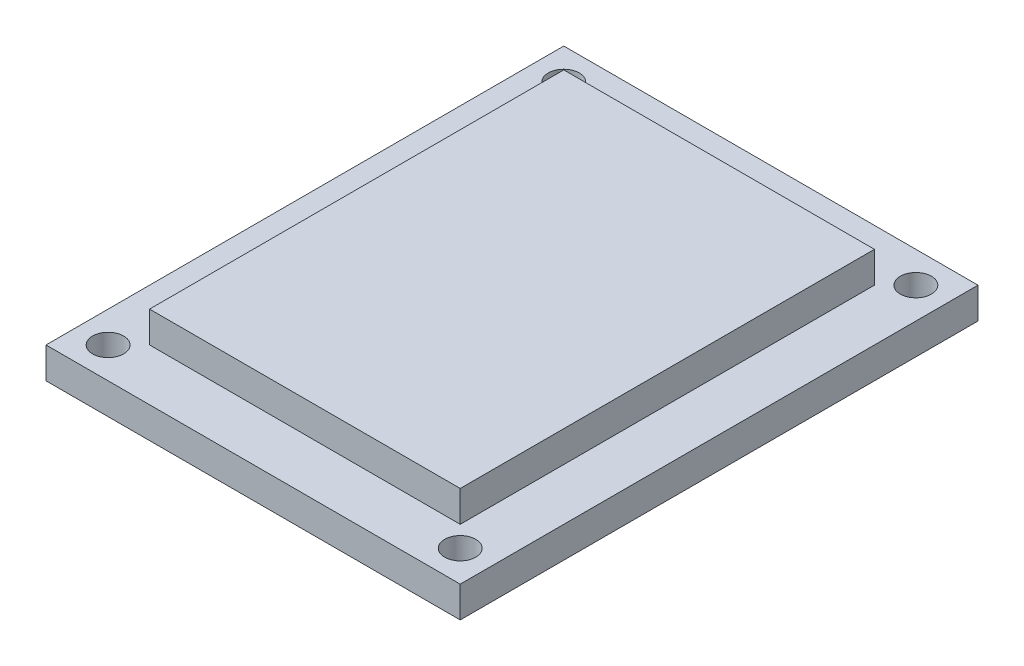
SolidWorks part; units mm, degrees
ref_plane "Front Plane" through (0, 0, 0) normal (0, 0, 1) x (1, 0, 0)
ref_plane "Top Plane" through (0, 0, 0) normal (0, 1, 0) x (1, 0, 0)
ref_plane "Right Plane" through (0, 0, 0) normal (1, 0, 0) x (0, 0, -1)
sketch "Sketch1" plane through (0, 0, 0) normal (0, 1, 0) x (1, 0, 0)
  line L1 (-15, -20) -> (15, -20)
  line L2 (-15, -20) -> (-15, 20)
  line L3 (-15, 20) -> (15, 20)
  line L4 (15, -20) -> (15, 20)
  line L5 (-15, -20) -> (15, 20) construction
  line L6 (-15, 20) -> (15, -20) construction
  point P0 (0, 0)
  dimension "D1" = 40
  dimension "D2" = 30
extrude "Boss-Extrude1" add sketch "Sketch1" along normal blind 3
sketch "Sketch2" plane through (0, 0, 0) normal (0, 1, 0) x (1, 0, 0)
  line L11 (17, -22) -> (-17, -22) construction
  line L12 (17, -22) -> (17, 22) construction
  line L13 (17, 22) -> (-17, 22) construction
  line L14 (20, -25) -> (20, 25)
  line L15 (-20, -25) -> (20, -25)
  line L16 (-20, 25) -> (-20, -25)
  line L17 (20, 25) -> (-20, 25)
  line L18 (20, -25) -> (20, 25)
  line L19 (-20, -25) -> (20, -25)
  line L20 (-20, 25) -> (-20, -25)
  line L21 (20, 25) -> (-20, 25)
  line L22 (-17, -22) -> (-17, 22) construction
  line L23 (17, -22) -> (-17, 22) construction
  line L24 (17, 22) -> (-17, -22) construction
  circle A0 centre (-17, 21.998) radius 1.5
  circle A1 centre (17, 22) radius 1.5
  circle A2 centre (17, -22) radius 1.5
  circle A3 centre (-17, -22) radius 1.5
  point P0 (0, 0)
  dimension "D2" = 3
  dimension "D3" = 3
  dimension "D4" = 3
  dimension "D1" = 5
extrude "Boss-Extrude2" add sketch "Sketch2" against normal blind 3
